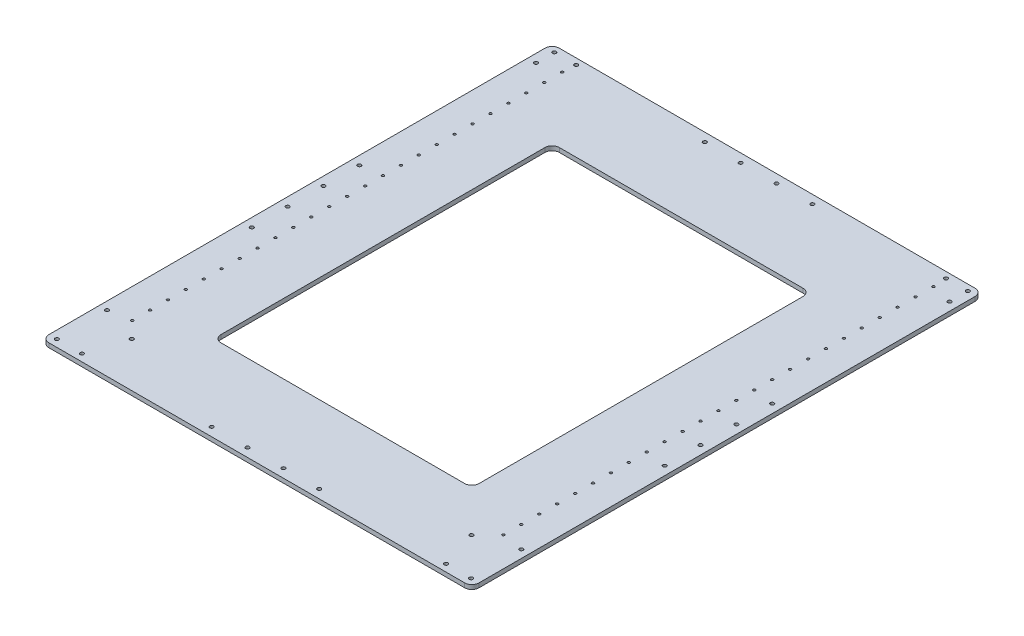
SolidWorks part; units mm, degrees
ref_plane "Front Plane" through (0, 0, 0) normal (0, 0, 1) x (1, 0, 0)
ref_plane "Top Plane" through (0, 0, 0) normal (0, 1, 0) x (1, 0, 0)
ref_plane "Right Plane" through (0, 0, 0) normal (1, 0, 0) x (0, 0, -1)
sketch "Sketch1" plane through (0, 0, 0) normal (0, 1, 0) x (1, 0, 0)
  line L0 (0, 0) -> (0, 645.6687) construction
  line L1 (-300, -365) -> (300, -365)
  line L2 (-300, -365) -> (-300, 365)
  line L3 (-300, 365) -> (300, 365)
  line L4 (300, -365) -> (300, 365)
  line L5 (-300, -365) -> (300, 365) construction
  line L6 (-300, 365) -> (300, -365) construction
  line L11 (-300, -300) -> (300, 300) construction
  line L12 (-300, 300) -> (300, -300) construction
  point P0 (0, 0)
  point P6 (0, 0)
  dimension "D1" = 730
  dimension "D2" = 600
extrude "Boss-Extrude1" add sketch "Sketch1" along normal blind 6
sketch "Sketch2" plane through (0, 6, 0) normal (0, 1, 0) x (1, 0, 0)
  line L0 (-300, 365) -> (-300, -365) construction
  line L1 (-265, 330) -> (-253, 330)
  line L2 (-265, 330) -> (-265, -290)
  line L3 (-265, -290) -> (-253, -290)
  line L4 (-253, 330) -> (-253, -290)
  line L5 (-259, 330) -> (-259, 320)
  circle A0 centre (-259, 320) radius 1.75
  dimension "D6" = 3.5
  dimension "D1" = 35
  dimension "D2" = 12
  dimension "D3" = 290
  dimension "D4" = 620
  dimension "D5" = 10
extrude "Cut-Extrude1" cut sketch "Sketch2" against normal through all
pattern_linear "LPattern1" count 25 spacing 25 along (0, 0, 1) of "Cut-Extrude1"
mirror "Mirror2" about plane through (0, 0, 0) normal (1, 0, 0) of "LPattern1", "Cut-Extrude1"
sketch "Sketch3" plane through (0, 6, 0) normal (0, 1, 0) x (1, 0, 0)
  line L0 (-300, 365) -> (-300, -365) construction
  line L1 (-289, -355) -> (-254, -355) construction
  line L2 (-289, -355) -> (-289, -285) construction
  line L3 (-289, -285) -> (-254, -285) construction
  line L4 (-254, -355) -> (-254, -285) construction
  line L5 (-300, -365) -> (300, -365) construction
  circle A0 centre (-289, -285) radius 2.55
  circle A2 centre (-254, -355) radius 2.55
  circle A3 centre (-289, -355) radius 2.55
  circle A4 centre (-236.98, -302.5) radius 2.55
  dimension "D5" = 5.1
  dimension "D6" = 5.1
  dimension "D9" = 5.1
  dimension "D1" = 35
  dimension "D2" = 70
  dimension "D3" = 11
  dimension "D4" = 10
  dimension "D7" = 17.5
  dimension "D8" = 52.02
extrude "Cut-Extrude2" cut sketch "Sketch3" against normal blind 13
mirror "Mirror3" about plane through (0, 0, 0) normal (1, 0, 0) of "Cut-Extrude2"
sketch "Sketch5" plane through (0, 6, 0) normal (0, 1, 0) x (1, 0, 0)
  line L0 (-265, 330) -> (-253, 330) construction
  line L1 (-280.98, 306) -> (-295.98, 306)
  line L2 (-280.98, 306) -> (-280.98, 346)
  line L3 (-280.98, 346) -> (-295.98, 346)
  line L4 (-295.98, 306) -> (-295.98, 346)
  line L5 (-280.98, 346) -> (-250.98, 346)
  line L6 (-280.98, 346) -> (-280.98, 331)
  line L7 (-280.98, 331) -> (-250.98, 331)
  line L8 (-250.98, 346) -> (-250.98, 331)
  line L10 (-250.98, 338.5) -> (-354.0628, 338.5) construction
  line L11 (-288.48, 306) -> (-288.48, 373.0529) construction
  line L12 (-259, 320) -> (-259, 373.0529) construction
  circle A0 centre (-288.48, 313) radius 2.55
  circle A1 centre (-257.98, 338.5) radius 2.55
  circle A2 centre (-288.48, 338.5) radius 2.55
  dimension "D7" = 5.1
  dimension "D8" = 5.1
  dimension "D11" = 0
  dimension "D13" = 5.1
  dimension "D1" = 15
  dimension "D2" = 15
  dimension "D3" = 1
  dimension "D4" = 30
  dimension "D5" = 40
  dimension "D6" = 29.48
  dimension "D9" = 7
  dimension "D10" = 7
  dimension "D12" = 0
extrude "Cut-Extrude4" cut sketch "Sketch5" against normal through all contours A0 | A1 | A2
mirror "Mirror5" about plane through (0, 0, 0) normal (1, 0, 0) of "Cut-Extrude4"
sketch "Sketch6" plane through (0, 6, 0) normal (0, 1, 0) x (1, 0, 0)
  line L0 (300, -365) -> (300, 365) construction
  line L1 (-300, 365) -> (300, 365)
  line L2 (-300, 365) -> (-300, 347)
  line L3 (-300, 347) -> (300, 347)
  line L4 (300, 365) -> (300, 347)
  dimension "D1" = 18
extrude "Cut-Extrude5" cut sketch "Sketch6" against normal up to surface (6 mm away) contours L4 L1 L2 L3 up to face at (288.48, 0, -310.45)
sketch "Sketch7" plane through (0, 6, 0) normal (0, 1, 0) x (1, 0, 0)
  line L0 (-300, 347) -> (300, 347) construction
  line L1 (-300, -9) -> (300, -9) construction
  line L2 (-300, 347) -> (-300, -365) construction
  line L3 (300, -365) -> (300, 347) construction
  line L4 (0, 347) -> (0, -9) construction
  circle A0 centre (-75, 335) radius 2.55
  circle A1 centre (-25, 335) radius 2.55
  circle A2 centre (25, 335) radius 2.55
  circle A3 centre (75, 335) radius 2.55
  circle A4 centre (75, -353) radius 2.55
  circle A5 centre (25, -353) radius 2.55
  circle A6 centre (-25, -353) radius 2.55
  circle A7 centre (-75, -353) radius 2.55
  dimension "D1" = 5.1
  dimension "D2" = 50
  dimension "D3" = 50
  dimension "D4" = 50
  dimension "D5" = 12
  dimension "D6" = 25
extrude "Cut-Extrude6" cut sketch "Sketch7" against normal up to next
sketch "Sketch8" plane through (0, 6, 0) normal (0, 1, 0) x (1, 0, 0)
  line L0 (-300, -9) -> (300, -9) construction
  line L1 (-300, 347) -> (-300, -365) construction
  line L2 (300, -365) -> (300, 347) construction
  line L3 (0, -365) -> (0, 347) construction
  line L4 (-300, -365) -> (300, -365) construction
  line L5 (-300, 347) -> (300, 347) construction
  circle A0 centre (288, 66) radius 2.55
  circle A4 centre (288, 16) radius 2.55
  circle A5 centre (288, -34) radius 2.55
  circle A6 centre (288, -84) radius 2.55
  dimension "D1" = 75
  dimension "D2" = 4
  dimension "D6" = 12
extrude "Cut-Extrude7" cut sketch "Sketch8" against normal up to next
mirror "Mirror6" about plane through (0, 0, 0) normal (1, 0, 0) of "Cut-Extrude7"
sketch "Sketch9" plane through (0, 6, 0) normal (0, 1, 0) x (1, 0, 0)
  line L0 (0, 347) -> (0, -365) construction
  line L1 (-300, 347) -> (300, 347) construction
  line L2 (-300, -365) -> (300, -365) construction
  line L3 (300, -9) -> (-300, -9) construction
  line L4 (300, -365) -> (300, 347) construction
  line L5 (-300, 347) -> (-300, -365) construction
  line L7 (-180, -245) -> (180, -245)
  line L8 (-180, -245) -> (-180, 227)
  line L9 (-180, 227) -> (180, 227)
  line L10 (180, -245) -> (180, 227)
  line L11 (-180, -245) -> (180, 227) construction
  line L12 (-180, 227) -> (180, -245) construction
  point P12 (0, -9)
  dimension "D1" = 120
  dimension "D2" = 120
extrude "Cut-Extrude8" cut sketch "Sketch9" against normal up to next
fillet "Fillet2" radius 10 8 edges at (300, 3, -347) (300, 3, 365) (-300, 3, 365) (-300, 3, -347) (-180, 3, -227) (180, 3, -227) (180, 3, 245) (-180, 3, 245)
